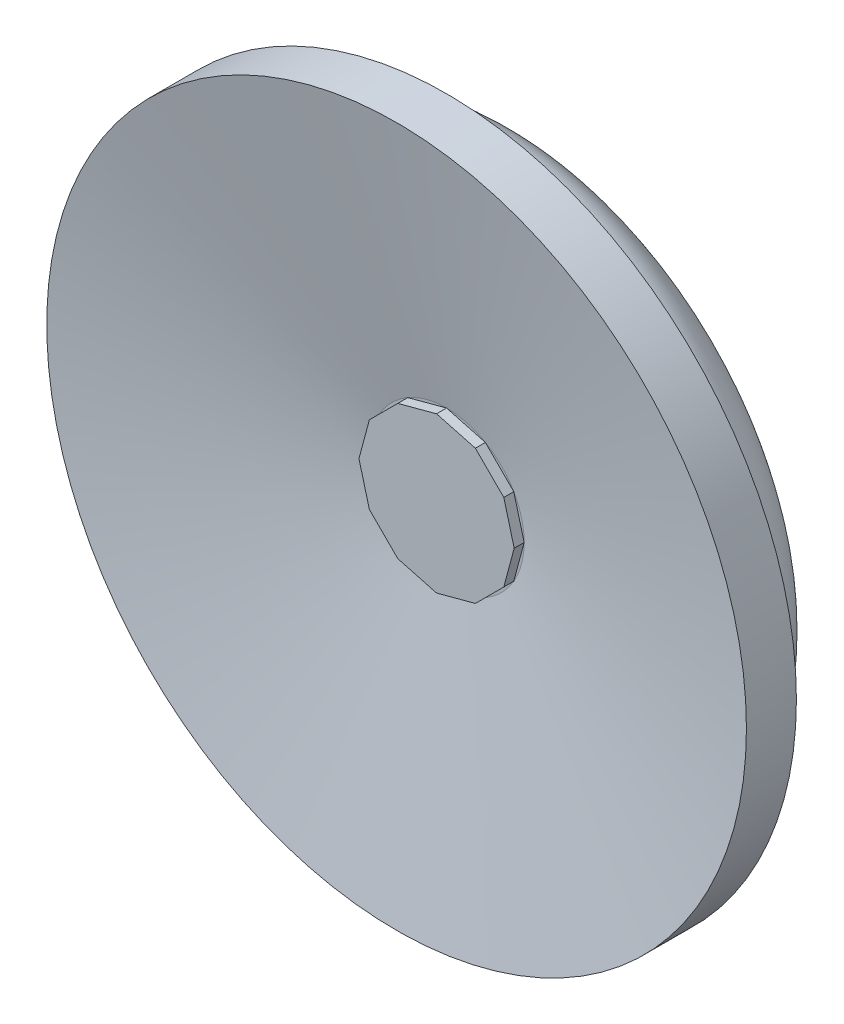
SolidWorks part; units mm, degrees
ref_plane "Front Plane" through (0, 0, 0) normal (0, 0, 1) x (1, 0, 0)
ref_plane "Top Plane" through (0, 0, 0) normal (0, 1, 0) x (1, 0, 0)
ref_plane "Right Plane" through (0, 0, 0) normal (1, 0, 0) x (0, 0, -1)
sketch "Sketch2" plane through (0, 0, 0) normal (0, 0, 1) x (1, 0, 0)
  circle A0 centre (0, 0) radius 70
extrude "Boss-Extrude2" add sketch "Sketch2" along normal blind 10 contours A0
sketch "Sketch3" plane through (0, 0, 0) normal (0, 0, 1) x (1, 0, 0)
  circle A0 centre (0, 0) radius 61
extrude "Boss-Extrude3" add sketch "Sketch3" against normal blind 15
ref_plane "Plane1" through (0, 0, 10) normal (0, 0, 1) x (1, 0, 0)
sketch "Sketch9" plane through (0, 0, 10) normal (0, 0, 1) x (1, 0, 0)
  line L1 (0, 15.5291) -> (-7.7646, 13.4486)
  line L2 (-7.7646, 13.4486) -> (-13.4486, 7.7646)
  line L3 (-13.4486, 7.7646) -> (-15.5291, 0)
  line L4 (-15.5291, 0) -> (-13.4486, -7.7646)
  line L5 (-13.4486, -7.7646) -> (-7.7646, -13.4486)
  line L6 (-7.7646, -13.4486) -> (0, -15.5291)
  line L7 (0, -15.5291) -> (7.7646, -13.4486)
  line L8 (7.7646, -13.4486) -> (13.4486, -7.7646)
  line L9 (13.4486, -7.7646) -> (15.5291, 0)
  line L10 (15.5291, 0) -> (13.4486, 7.7646)
  line L11 (13.4486, 7.7646) -> (7.7646, 13.4486)
  line L12 (7.7646, 13.4486) -> (0, 15.5291)
  circle A0 centre (0, 0) radius 15 construction
extrude "Cut-Extrude2" cut sketch "Sketch9" against normal blind 10
sketch "Sketch10" plane through (0, 0, 0) normal (0, 1, 0) x (1, 0, 0)
  line L0 (-15.5291, 0) -> (-70, -10)
  line L1 (70, 0) -> (-70, 0) construction
  line L2 (61, 0) -> (-61, 0) construction
  line L3 (-77, -10) -> (77, -10) construction
  line L4 (-70, -10) -> (-15.5291, -10)
  line L5 (-15.5291, -10) -> (-15.5291, 0)
  line L6 (0, -10) -> (0, 0)
  line L7 (0, 0) -> (0, -10) construction
  line L8 (-15.5291, 0) -> (0, 0)
  line L9 (-15.5291, -10) -> (0, -10)
revolve "Cut-Revolve7" cut sketch "Sketch10" angle 360 about L6
ref_plane "Plane2" through (0, 0, 0) normal (0, 0, 1) x (1, 0, 0)
sketch "Sketch14" plane through (0, 0, 0) normal (0, 0, 1) x (1, 0, 0)
  line L1 (0, 15.5291) -> (-7.7646, 13.4486)
  line L2 (-7.7646, 13.4486) -> (-13.4486, 7.7646)
  line L3 (-13.4486, 7.7646) -> (-15.5291, 0)
  line L4 (-15.5291, 0) -> (-13.4486, -7.7646)
  line L5 (-13.4486, -7.7646) -> (-7.7646, -13.4486)
  line L6 (-7.7646, -13.4486) -> (0, -15.5291)
  line L7 (0, -15.5291) -> (7.7646, -13.4486)
  line L8 (7.7646, -13.4486) -> (13.4486, -7.7646)
  line L9 (13.4486, -7.7646) -> (15.5291, 0)
  line L10 (15.5291, 0) -> (13.4486, 7.7646)
  line L11 (13.4486, 7.7646) -> (7.7646, 13.4486)
  line L12 (7.7646, 13.4486) -> (0, 15.5291)
  circle A0 centre (0, 0) radius 15 construction
extrude "Boss-Extrude4" add sketch "Sketch14" along normal blind 2
ref_plane "Plane3" through (0, 0, -15) normal (0, 0, -1) x (-1, 0, 0)
sketch "Sketch19" plane through (0, 0, -15) normal (0, 0, -1) x (-1, 0, 0)
  circle A0 centre (0, 0) radius 2
extrude "Boss-Extrude5" add sketch "Sketch19" along normal blind 16.7
ref_plane "Plane6" through (0, 0, -34.3) normal (0, 0, -1) x (-1, 0, 0)
sketch "Sketch22" plane through (0, 0, -34.3) normal (0, 0, -1) x (-1, 0, 0)
  line L0 (0, -3.7) -> (0, 3.7)
  arc A0 (0, 3.7) -> (0, -3.7) centre (0, 0) ccw
revolve "Revolve2" add sketch "Sketch22" angle 360 about L0
fillet "Fillet1" radius 10 3 edges at (61, 0, -15) (-2, 0, -31.1871) (2, 0, -15)
